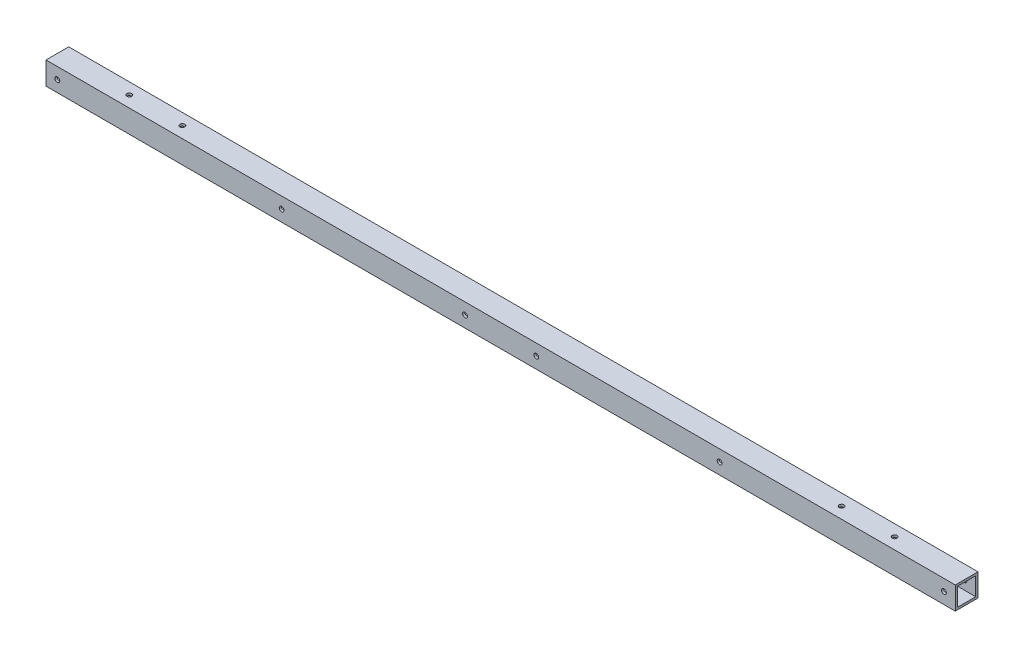
SolidWorks part; units mm, degrees
ref_plane "正面" through (0, 0, 0) normal (0, 0, 1) x (1, 0, 0)
ref_plane "平面" through (0, 0, 0) normal (0, 1, 0) x (1, 0, 0)
ref_plane "右側面" through (0, 0, 0) normal (1, 0, 0) x (0, 0, -1)
sketch "ｽｹｯﾁ2" plane through (0, 0, 0) normal (0, 0, 1) x (1, 0, 0)
  line L0 (0, -7.5) -> (600, -7.5) construction
  line L1 (0, 0) -> (600, 0)
  line L2 (0, 0) -> (0, -15)
  line L3 (0, -15) -> (600, -15)
  line L4 (600, 0) -> (600, -15)
  circle A0 centre (7.5, -7.5) radius 1.6
  circle A1 centre (155.5, -7.5) radius 1.6
  circle A2 centre (444.5, -7.5) radius 1.6
  circle A3 centre (592.5, -7.5) radius 1.6
  dimension "D1" = 7.5
  dimension "D3" = 148
  dimension "D4" = 3.2
  dimension "D5" = 7.5
  dimension "D6" = 148
  dimension "D7" = 600
  dimension "D2" = 15
extrude "ﾎﾞｽ - 押し出し1" add sketch "ｽｹｯﾁ2" along normal blind 15
sketch "ｽｹｯﾁ3" plane through (600, 0, 0) normal (1, 0, 0) x (0, 0, -1)
  line L8 (-1.5, -13.5) -> (-1.5, -1.5)
  line L9 (-1.5, -1.5) -> (-13.5, -1.5)
  line L10 (-13.5, -1.5) -> (-13.5, -13.5)
  line L11 (-13.5, -13.5) -> (-1.5, -13.5)
  line L12 (-1.5, -13.5) -> (-1.5, -1.5)
  line L13 (-1.5, -1.5) -> (-13.5, -1.5)
  line L14 (-13.5, -1.5) -> (-13.5, -13.5)
  line L15 (-13.5, -13.5) -> (-1.5, -13.5)
  dimension "D1" = 1.5
extrude "ｶｯﾄ - 押し出し1" cut sketch "ｽｹｯﾁ3" against normal through all
sketch "ｽｹｯﾁ4" plane through (0, 0, 0) normal (0, 1, 0) x (1, 0, 0)
  line L0 (600, -7.5) -> (0, -7.5) construction
  line L1 (600, -15) -> (600, 0) construction
  line L2 (0, -15) -> (0, 0) construction
  circle A0 centre (55, -7.5) radius 1.6
  circle A1 centre (545, -7.5) radius 1.6
  dimension "D1" = 55
  dimension "D2" = 55
  dimension "D3" = 3.2
extrude "ｶｯﾄ - 押し出し2" [suppressed] cut sketch "ｽｹｯﾁ4" against normal through all
sketch "ｽｹｯﾁ5" plane through (0, -15, 0) normal (0, -1, 0) x (1, 0, 0)
  line L0 (0, 7.5) -> (600, 7.5) construction
  line L1 (0, 15) -> (0, 0) construction
  line L2 (600, 15) -> (600, 0) construction
  circle A0 centre (552.5, 7.5) radius 1.6
  circle A1 centre (517.5, 7.5) radius 1.6
  circle A2 centre (47.5, 7.5) radius 1.6
  circle A3 centre (82.5, 7.5) radius 1.6
  dimension "D1" = 47.5
  dimension "D2" = 35
  dimension "D3" = 3.2
  dimension "D4" = 47.5
  dimension "D5" = 35
extrude "ｶｯﾄ - 押し出し3" cut sketch "ｽｹｯﾁ5" against normal through all
chamfer "面取り1" [suppressed] distance 1 angle 45
sketch "ｽｹｯﾁ6" plane through (0, 0, 15) normal (0, 0, 1) x (1, 0, 0)
  line L0 (300, 0) -> (300, -15) construction
  line L1 (600, 0) -> (0, 0) construction
  line L2 (0, -15) -> (600, -15) construction
  line L3 (323.5, -7.5) -> (276.5, -7.5) construction
  circle A0 centre (276.5, -7.5) radius 1.6
  circle A1 centre (323.5, -7.5) radius 1.6
  point P9 (300, -7.5)
  dimension "D1" = 3.2
  dimension "D2" = 47
extrude "ｶｯﾄ - 押し出し4" cut sketch "ｽｹｯﾁ6" against normal through all
